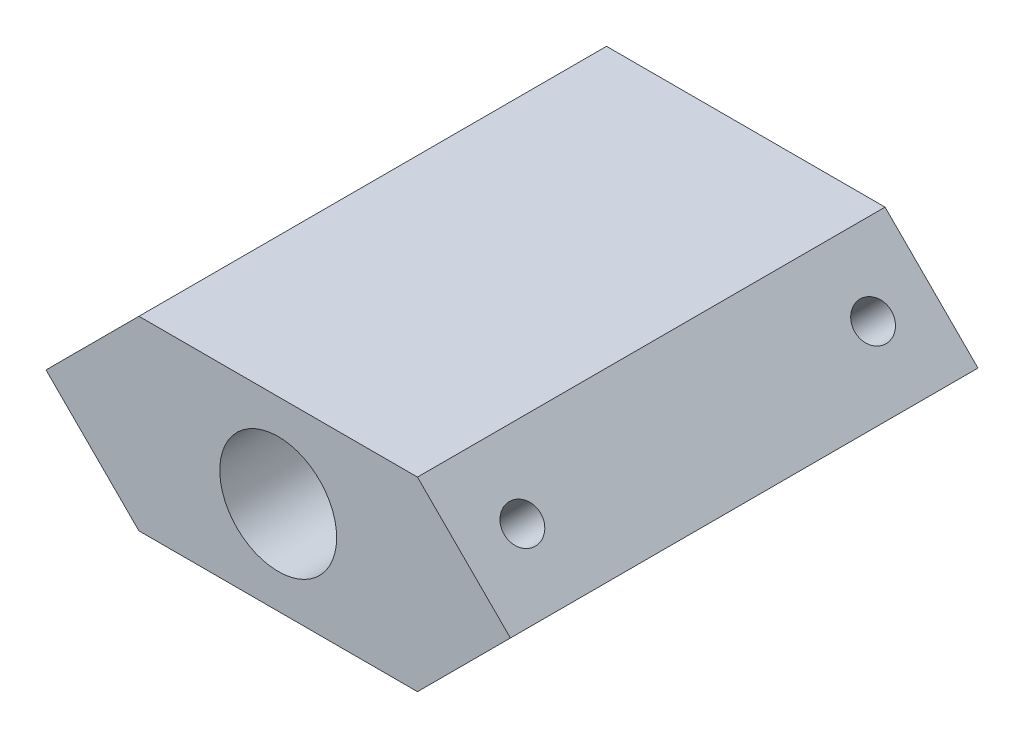
SolidWorks part; units mm, degrees
material "Alliage 1060"
ref_plane "Plan de face" through (0, 0, 0) normal (0, 0, 1) x (1, 0, 0)
ref_plane "Plan de dessus" through (0, 0, 0) normal (0, 1, 0) x (1, 0, 0)
ref_plane "Plan de droite" through (0, 0, 0) normal (1, 0, 0) x (0, 0, -1)
sketch "Esquisse1" plane through (0, 0, 0) normal (0, 0, 1) x (1, 0, 0)
  line L1 (0, 0) -> (100.91, 0)
  line L2 (0, 0) -> (0, 40.386)
  line L3 (0, 40.386) -> (100.91, 40.386)
  line L4 (100.91, 0) -> (100.91, 40.386)
  dimension "D1" = 40.386
  dimension "D2" = 100.91
extrude "Boss.-Extru.1" add sketch "Esquisse1" along normal blind 101.6
sketch "Esquisse3" plane through (0, 0, 0) normal (0, 0, -1) x (-1, 0, 0)
  line L0 (-100.91, 20.193) -> (-80.717, 0)
  line L1 (-100.91, 0) -> (-100.91, 40.386) construction
  line L2 (0, 0) -> (-100.91, 0) construction
  line L3 (-80.717, 0) -> (-100.91, 0)
  line L4 (-100.91, 0) -> (-100.91, 20.193)
  line L6 (-50.455, 40.386) -> (-50.455, 0) construction
  line L7 (-100.91, 40.386) -> (0, 40.386) construction
  line L8 (0, 0) -> (0, 20.193)
  line L9 (-20.193, 0) -> (0, 0)
  line L10 (0, 20.193) -> (-20.193, 0)
extrude "Enlèv. mat.-Extru.1" cut sketch "Esquisse3" against normal blind 101.6
sketch "Esquisse4" plane through (0, 0, 0) normal (0, 0, -1) x (-1, 0, 0)
  line L0 (-100.91, 20.193) -> (-80.717, 40.386)
  line L1 (-100.91, 40.386) -> (0, 40.386) construction
  line L2 (-80.717, 40.386) -> (-100.91, 40.386)
  line L3 (-100.91, 40.386) -> (-100.91, 20.193)
  line L4 (-50.455, 40.386) -> (-50.455, 0) construction
  line L5 (-20.193, 0) -> (-80.717, 0) construction
  line L6 (0, 40.386) -> (0, 20.193)
  line L7 (-20.193, 40.386) -> (0, 40.386)
  line L8 (0, 20.193) -> (-20.193, 40.386)
extrude "Enlèv. mat.-Extru.2" cut sketch "Esquisse4" against normal through all
sketch "Esquisse5" plane through (60.5515, 60.5515, 0) normal (0.7071, 0.7071, 0) x (0, 0, -1)
  line L0 (-88.9, -28.5183) -> (-88.9, -42.7969) construction
  line L1 (-101.6, -28.5183) -> (0, -28.5183) construction
  line L2 (-88.9, -42.7969) -> (-88.9, -57.0755) construction
  line L3 (-101.6, -57.0755) -> (0, -57.0755) construction
  line L4 (-88.9, -42.7969) -> (-101.6, -42.7969) construction
  line L5 (-101.6, -57.0755) -> (-101.6, -28.5183) construction
  line L6 (-12.7, -42.7969) -> (0, -42.7969) construction
  line L7 (0, -57.0755) -> (0, -28.5183) construction
  circle A0 centre (-88.9, -42.7969) radius 3.975
  circle A1 centre (-12.7, -42.7969) radius 3.975
  dimension "D1" = 7.95
  dimension "D2" = 12.7
extrude "Enlèv. mat.-Extru.3" cut sketch "Esquisse5" against normal blind 20
sketch "Esquisse6" plane through (10.0965, 10.0965, 0) normal (-0.7071, -0.7071, 0) x (0, 0, 1)
  line L0 (12.7, 0) -> (0, 0) construction
  line L1 (0, 14.2786) -> (0, -14.2786) construction
  line L2 (88.9, 0) -> (101.6, 0) construction
  line L3 (101.6, 14.2786) -> (101.6, -14.2786) construction
  line L4 (12.7, 14.2786) -> (12.7, 0) construction
  line L5 (101.6, 14.2786) -> (0, 14.2786) construction
  line L6 (12.7, 0) -> (12.7, -14.2786) construction
  line L7 (101.6, -14.2786) -> (0, -14.2786) construction
  circle A0 centre (12.7, 0) radius 3.937
  circle A1 centre (88.9, 0) radius 3.937
  dimension "D1" = 7.874
  dimension "D2" = 12.7
extrude "Enlèv. mat.-Extru.4" cut sketch "Esquisse6" against normal blind 20
sketch "Esquisse7" plane through (-10.0965, 10.0965, 0) normal (-0.7071, 0.7071, 0) x (0, 0, 1)
  line L0 (31.75, 42.8358) -> (31.75, 28.5572) construction
  line L1 (101.6, 42.8358) -> (0, 42.8358) construction
  line L2 (31.75, 28.5572) -> (31.75, 14.2786) construction
  line L3 (101.6, 14.2786) -> (0, 14.2786) construction
  line L4 (31.75, 28.5572) -> (0, 28.5572) construction
  line L5 (0, 42.8358) -> (0, 14.2786) construction
  line L6 (69.85, 28.5572) -> (101.6, 28.5572) construction
  line L7 (101.6, 42.8358) -> (101.6, 14.2786) construction
  circle A0 centre (31.75, 28.5572) radius 3.937
  circle A1 centre (69.85, 28.5572) radius 3.937
  dimension "D1" = 7.874
  dimension "D2" = 31.75
extrude "Enlèv. mat.-Extru.5" cut sketch "Esquisse7" against normal blind 20
sketch "Esquisse8" plane through (40.3585, -40.3585, 0) normal (0.7071, -0.7071, 0) x (0, 0, -1)
  line L0 (-69.85, 71.3541) -> (-101.6, 71.3541) construction
  line L1 (-101.6, 57.0755) -> (-101.6, 85.6328) construction
  line L2 (-31.75, 71.3541) -> (0, 71.3541) construction
  line L3 (0, 57.0755) -> (0, 85.6328) construction
  line L4 (-69.85, 85.6328) -> (-69.85, 71.3541) construction
  line L5 (-101.6, 85.6328) -> (0, 85.6328) construction
  line L6 (-69.85, 71.3541) -> (-69.85, 57.0755) construction
  line L7 (-101.6, 57.0755) -> (0, 57.0755) construction
  circle A0 centre (-69.85, 71.3541) radius 3.937
  circle A1 centre (-31.75, 71.3541) radius 3.937
  dimension "D1" = 7.874
  dimension "D2" = 31.75
extrude "Enlèv. mat.-Extru.6" cut sketch "Esquisse8" against normal blind 20
sketch "Esquisse9" plane through (0, 0, 0) normal (0, 0, -1) x (-1, 0, 0)
  line L0 (-80.717, 40.386) -> (-20.193, 0) construction
  line L1 (-80.717, 0) -> (-20.193, 40.386) construction
  circle A0 centre (-50.455, 20.193) radius 6.35
  dimension "D1" = 12.7
extrude "Enlèv. mat.-Extru.7" cut sketch "Esquisse9" against normal through all
sketch "Esquisse10" plane through (0, 0, 0) normal (0, 0, -1) x (-1, 0, 0)
  circle A0 centre (-50.455, 20.193) radius 9.525
  dimension "D1" = 19.05
extrude "Enlèv. mat.-Extru.8" cut sketch "Esquisse10" against normal blind 7.35
sketch "Esquisse11" plane through (0, 0, 101.6) normal (0, 0, 1) x (1, 0, 0)
  circle A0 centre (50.455, 20.193) radius 12.7
  dimension "D1" = 25.4
extrude "Enlèv. mat.-Extru.9" cut sketch "Esquisse11" against normal blind 20.65
